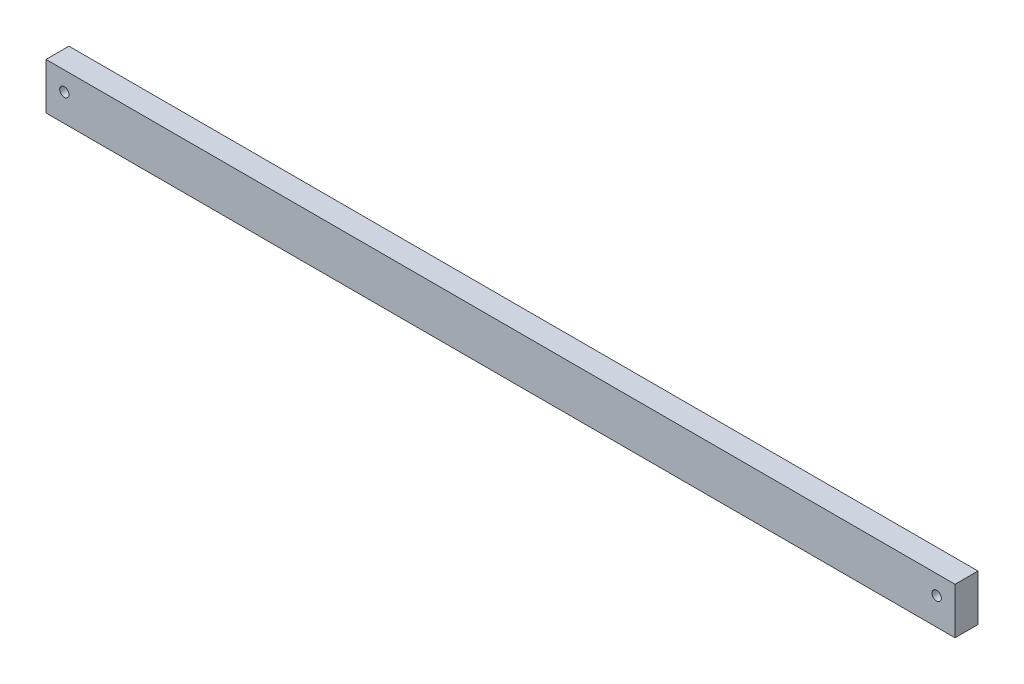
SolidWorks part; units mm, degrees
ref_plane "Front Plane" through (0, 0, 0) normal (0, 0, 1) x (1, 0, 0)
ref_plane "Top Plane" through (0, 0, 0) normal (0, 1, 0) x (1, 0, 0)
ref_plane "Right Plane" through (0, 0, 0) normal (1, 0, 0) x (0, 0, -1)
sketch "Sketch1" plane through (0, 0, 0) normal (0, 1, 0) x (1, 0, 0)
  line L1 (-990, 50) -> (990, 50)
  line L2 (-990, 50) -> (-990, 0)
  line L3 (-990, 0) -> (990, 0)
  line L4 (990, 50) -> (990, 0)
  dimension "D1" = 1980
  dimension "D2" = 50
extrude "Boss-Extrude1" add sketch "Sketch1" along normal blind 101.05
sketch "Sketch2" plane through (0, 0, 0) normal (0, 0, 1) x (1, 0, 0)
  line L2 (-990, 0) -> (990, 0) construction
  line L3 (0, 0) -> (0, 101.05) construction
  line L4 (-990, 101.05) -> (990, 101.05) construction
  circle A0 centre (-950, 59.525) radius 10.16
  circle A1 centre (950, 59.525) radius 10.16
  dimension "D1" = 20.32
  dimension "D2" = 950
  dimension "D3" = 59.525
extrude "Cut-Extrude1" cut sketch "Sketch2" against normal through all from surface at 0 starting at face at (0, 50.525, 0)
